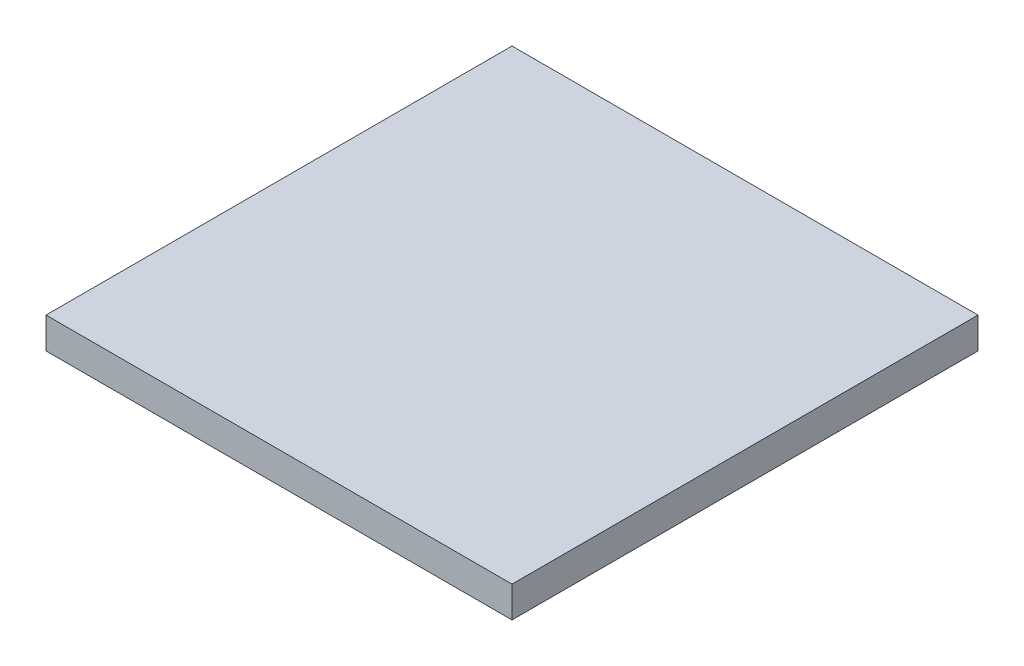
SolidWorks part; units mm, degrees
ref_plane "Front Plane" through (0, 0, 0) normal (0, 0, 1) x (1, 0, 0)
ref_plane "Top Plane" through (0, 0, 0) normal (0, 1, 0) x (1, 0, 0)
ref_plane "Right Plane" through (0, 0, 0) normal (1, 0, 0) x (0, 0, -1)
sketch "Sketch1" plane through (0, 0, 0) normal (0, 1, 0) x (1, 0, 0)
  line L1 (0, 0) -> (15, 0)
  line L2 (0, 0) -> (0, 15)
  line L3 (0, 15) -> (15, 15)
  line L4 (15, 0) -> (15, 15)
  dimension "D1" = 15
  dimension "D2" = 15
extrude "Boss-Extrude1" add sketch "Sketch1" along normal blind 1
